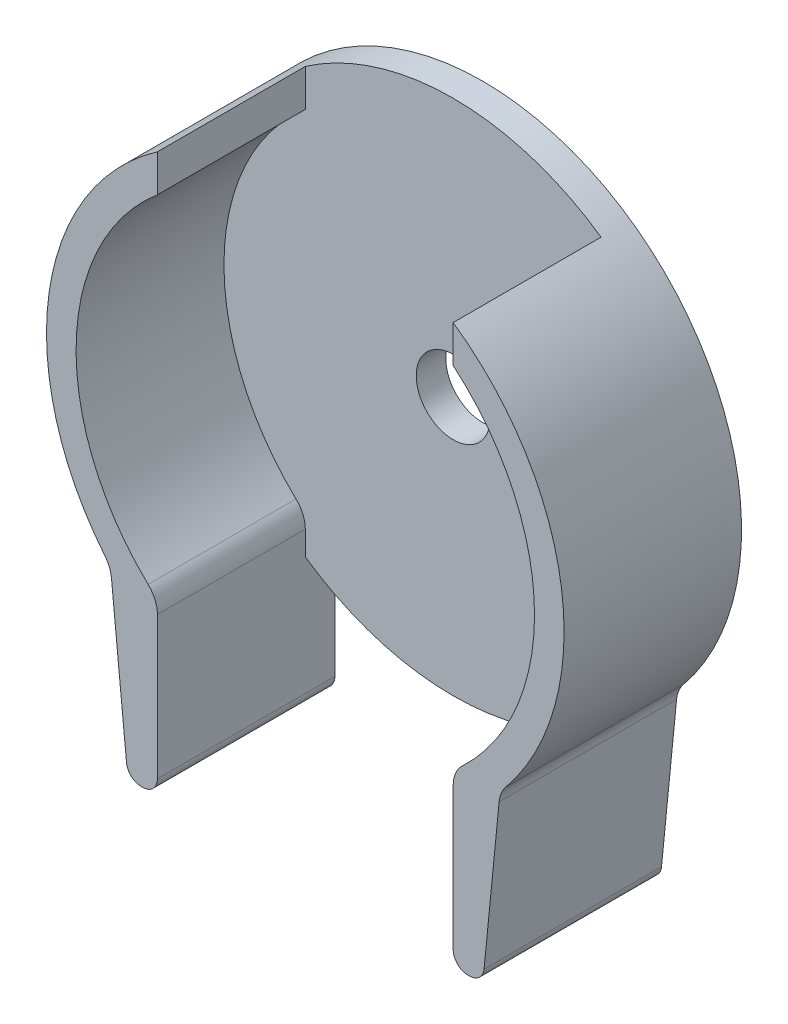
SolidWorks part; units mm, degrees
material "1060 Alloy"
ref_plane "Front Plane" through (0, 0, 0) normal (0, 0, 1) x (1, 0, 0)
ref_plane "Top Plane" through (0, 0, 0) normal (0, 1, 0) x (1, 0, 0)
ref_plane "Right Plane" through (0, 0, 0) normal (1, 0, 0) x (0, 0, -1)
sketch "Sketch1" plane through (0, 0, 0) normal (0, 0, 1) x (1, 0, 0)
  circle A0 centre (0, 0) radius 17.5
  dimension "D1" = 35
extrude "Boss-Extrude1" add sketch "Sketch1" along normal blind 12
shell "Shell4" thickness 2
sketch "Sketch3" plane through (0, 0, 0) normal (0, 0, 1) x (1, 0, 0)
  circle A0 centre (0, 0) radius 2.5
extrude "Cut-Extrude1" cut sketch "Sketch3" along normal through all both and the other way through all
sketch "Sketch4" plane through (0, 0, 0) normal (0, 1, 0) x (1, 0, 0)
  line L0 (0, 10.3606) -> (0, -25.7956) construction
  line L1 (-10, -2) -> (-10, -26.9407)
  line L2 (10, -2) -> (10, -26.9407)
  line L3 (-10, -2) -> (10, -2)
  line L4 (-10, -26.9407) -> (10, -26.9407)
  line L5 (-17.5, -12) -> (17.5, -12) construction
  dimension "D1" = 20
  dimension "D2" = 10
  dimension "D3" = 2
  dimension "D4" = 14.9407
extrude "Cut-Extrude2" cut sketch "Sketch4" against normal through all both and the other way through all
sketch "Sketch7" plane through (0, 0, 12) normal (0, 0, 1) x (1, 0, 0)
  line L0 (-10, -14.3614) -> (-10, -23.3578)
  line L1 (-10, -23.3578) -> (-12, -23.3578)
  line L2 (-12, -23.3578) -> (-13.1693, -11.5248)
  line L3 (-13.1693, -11.5248) -> (-10, -14.3614)
  line L4 (10, -14.3614) -> (10, -23.3578)
  line L5 (10, -23.3578) -> (12, -23.3578)
  line L6 (12, -23.3578) -> (13.1693, -11.5248)
  line L7 (10, -14.3614) -> (13.1693, -11.5248)
  arc A0 (-10, 14.3614) -> (-10, -14.3614) centre (0, 0) ccw construction
  arc A1 (10, -14.3614) -> (10, 14.3614) centre (0, 0) ccw construction
  point P12 (0, 0)
  point P17 (0, 0)
  dimension "D1" = 2
extrude "Boss-Extrude2" add sketch "Sketch7" against normal blind 12
fillet "Fillet1" radius 2 2 edges at (10, -11.8427, 7) (-10, -11.8427, 7)
fillet "Fillet2" radius 2 2 edges at (13.1693, -11.5248, 6) (-13.1693, -11.5248, 6)
fillet "Fillet5" radius 1 4 edges at (10, -23.3578, 6) (12, -23.3578, 6) (-10, -23.3578, 6) (-12, -23.3578, 6)
